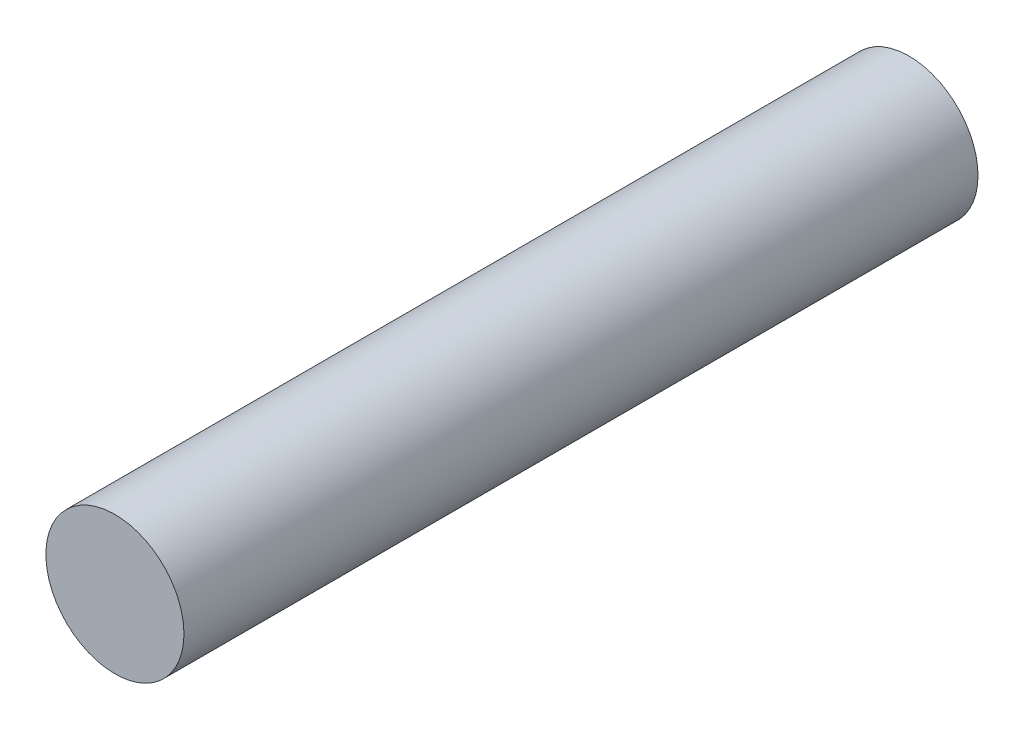
SolidWorks part; units mm, degrees
ref_plane "Front Plane" through (0, 0, 0) normal (0, 0, 1) x (1, 0, 0)
ref_plane "Top Plane" through (0, 0, 0) normal (0, 1, 0) x (1, 0, 0)
ref_plane "Right Plane" through (0, 0, 0) normal (1, 0, 0) x (0, 0, -1)
sketch "Sketch1" plane through (0, 0, 0) normal (0, 0, 1) x (1, 0, 0)
  circle A0 centre (0, 0) radius 2
  dimension "D1" = 4
extrude "Boss-Extrude1" add sketch "Sketch1" along normal blind 23
